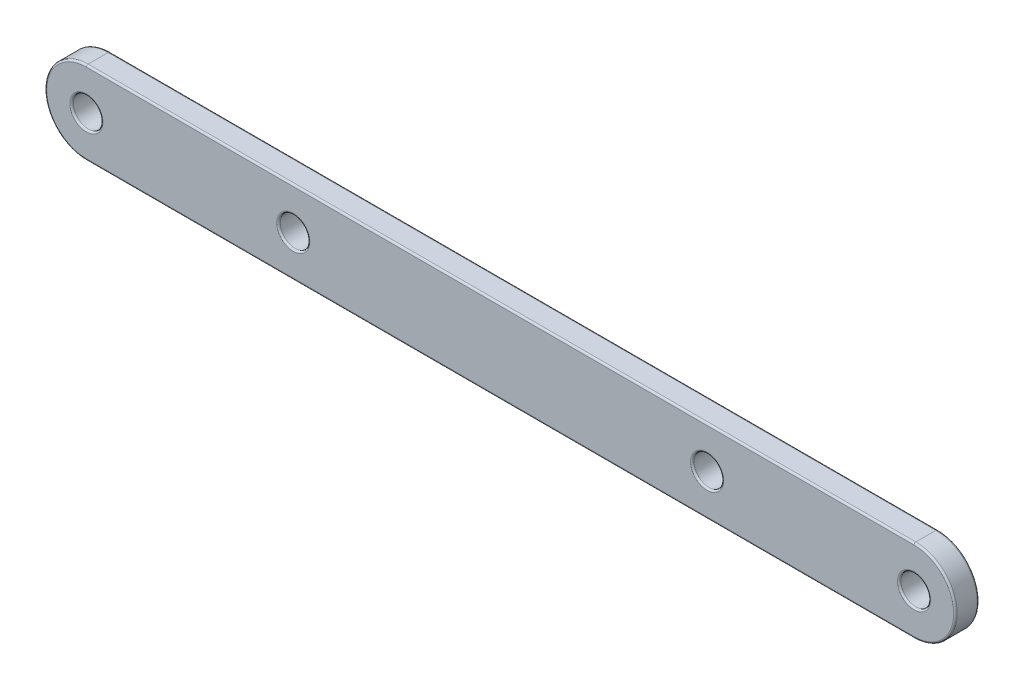
SolidWorks part; units mm, degrees
ref_plane "Front Plane" through (0, 0, 0) normal (0, 0, 1) x (1, 0, 0)
ref_plane "Top Plane" through (0, 0, 0) normal (0, 1, 0) x (1, 0, 0)
ref_plane "Right Plane" through (0, 0, 0) normal (1, 0, 0) x (0, 0, -1)
sketch "Sketch1" plane through (0, 0, 0) normal (0, 0, 1) x (1, 0, 0)
  line L0 (0, 0) -> (0, -27.743) construction
  line L1 (35, 3.5) -> (-35, 3.5)
  line L2 (-35, -3.5) -> (35, -3.5)
  circle A0 centre (-17.5, 0) radius 1.25
  circle A1 centre (-35, 0) radius 1.25
  circle A2 centre (35, 0) radius 1.25
  circle A3 centre (17.5, 0) radius 1.25
  arc A4 (-35, 3.5) -> (-35, -3.5) centre (-35, 0) ccw
  arc A5 (35, 3.5) -> (35, -3.5) centre (35, 0) cw
  circle A6 centre (-35, 0) radius 3.5 construction
  circle A7 centre (35, 0) radius 3.5 construction
  point P15 (35, 1.156)
  point P20 (0, 0)
  dimension "D3" = 2.5
  dimension "D1" = 70
  dimension "D2" = 17.5
  dimension "D4" = 2.25
  dimension "D5" = 2.25
extrude "Boss-Extrude1" add sketch "Sketch1" along normal blind 2
fillet "Fillet1" radius 0.15 16 edges at (16.25, 0, 0) (16.25, 0, 2) (33.75, 0, 0) (33.75, 0, 2) (-33.75, 0, 0) (-33.75, 0, 2) (-16.25, 0, 0) (-16.25, 0, 2) (-38.5, 0, 0) (0, -3.5, 0) (38.5, 0, 0) (0, 3.5, 0) (-38.5, 0, 2) (0, -3.5, 2) (38.5, 0, 2) (0, 3.5, 2)
